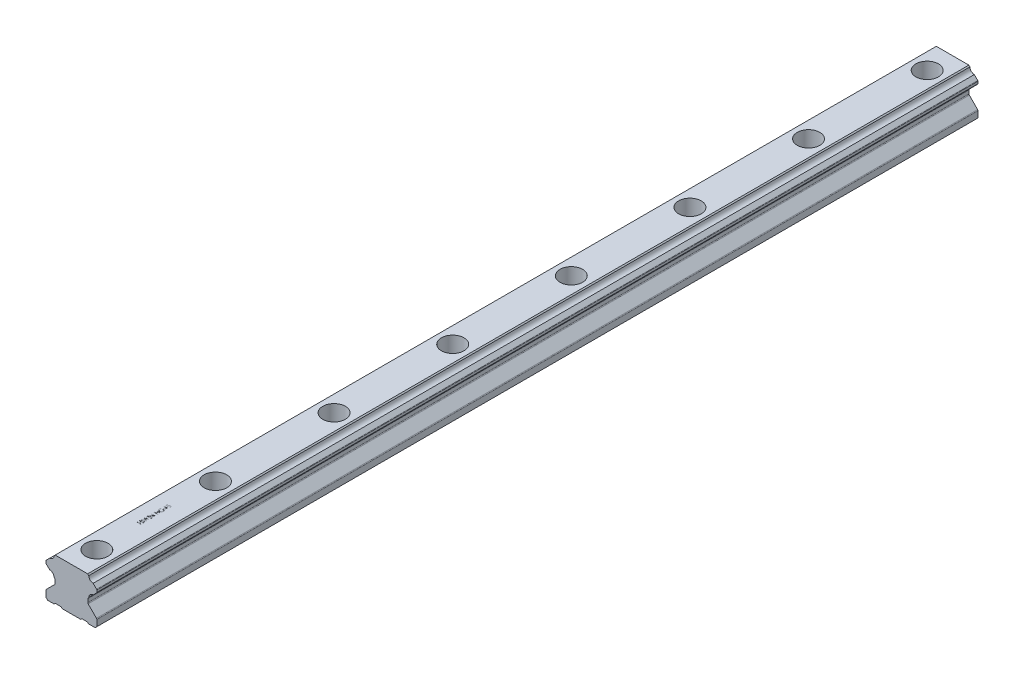
SolidWorks part; units mm, degrees
material "镀铬不锈钢"
ref_plane "前视基准面" through (0, 0, 0) normal (0, 0, 1) x (1, 0, 0)
ref_plane "上视基准面" through (0, 0, 0) normal (0, 1, 0) x (1, 0, 0)
ref_plane "右视基准面" through (0, 0, 0) normal (1, 0, 0) x (0, 0, -1)
sketch "草图1" plane through (0, 0, 0) normal (0, 0, 1) x (1, 0, 0)
  line L28 (-19.2333, 33.1666) -> (-22.2653, 30.1347)
  line L29 (-14.4996, 19.0026) -> (-14.4996, 15.9974)
  line L30 (14.5004, 15.9974) -> (14.5004, 19.0026)
  line L31 (15.3339, 37.0668) -> (14.4007, 38)
  line L32 (-22.2653, 27.2653) -> (-19.2344, 24.2344)
  line L33 (22.5004, 27.831) -> (22.5004, 29.569)
  line L34 (14.8518, 19.8511) -> (15.3339, 20.3331)
  line L35 (22.2661, 30.1347) -> (19.2341, 33.1666)
  line L36 (-22.4996, 29.569) -> (-22.4996, 27.831)
  line L37 (-15.3331, 20.3331) -> (-14.8511, 19.8511)
  line L38 (9.25, 1) -> (14.25, 1)
  line L39 (-14.25, 1) -> (-9.25, 1)
  line L40 (14.25, 1) -> (15.25, 0)
  line L41 (21.0004, 0) -> (22.5004, 1.5)
  line L42 (22.1489, 7.8518) -> (14.8518, 15.1489)
  line L43 (8.25, 0) -> (9.25, 1)
  line L44 (-22.4996, 1.5) -> (-20.9996, 0)
  line L45 (-15.25, 0) -> (-14.25, 1)
  line L46 (-8.25, 0) -> (8.25, 0)
  line L47 (15.25, 0) -> (21.0004, 0)
  line L48 (-14.8511, 15.1489) -> (-22.1482, 7.8518)
  line L49 (-22.4996, 7.0033) -> (-22.4996, 1.5)
  line L50 (-20.9996, 0) -> (-15.25, 0)
  line L51 (-9.25, 1) -> (-8.25, 0)
  line L52 (22.5004, 1.5) -> (22.5004, 7.0033)
  line L53 (14.4007, 38) -> (-14.4, 38)
  line L54 (-14.4, 38) -> (-15.3331, 37.0668)
  line L55 (19.2351, 24.2344) -> (22.2661, 27.2653)
  arc A14 (-19.2333, 33.1666) -> (-15.3331, 37.0668) centre (-19.3319, 37.1654) ccw
  arc A15 (-15.3331, 20.3331) -> (-19.2344, 24.2344) centre (-19.3319, 20.2356) ccw
  arc A16 (14.8518, 19.8511) -> (14.5004, 19.0026) centre (15.7004, 19.0026) ccw
  arc A17 (22.5004, 7.0033) -> (22.1489, 7.8518) centre (21.3004, 7.0033) ccw
  arc A18 (19.2351, 24.2344) -> (15.3339, 20.3331) centre (19.3327, 20.2356) ccw
  arc A19 (22.5004, 29.569) -> (22.2661, 30.1347) centre (21.7004, 29.569) ccw
  arc A20 (-22.4996, 27.831) -> (-22.2653, 27.2653) centre (-21.6996, 27.831) ccw
  arc A21 (-14.8511, 15.1489) -> (-14.4996, 15.9974) centre (-15.6996, 15.9974) ccw
  arc A22 (14.5004, 15.9974) -> (14.8518, 15.1489) centre (15.7004, 15.9974) ccw
  arc A23 (15.3339, 37.0668) -> (19.2341, 33.1666) centre (19.3327, 37.1654) ccw
  arc A24 (-22.2653, 30.1347) -> (-22.4996, 29.569) centre (-21.6996, 29.569) ccw
  arc A25 (-22.1482, 7.8518) -> (-22.4996, 7.0033) centre (-21.2996, 7.0033) ccw
  arc A26 (22.2661, 27.2653) -> (22.5004, 27.831) centre (21.7004, 27.831) ccw
  arc A27 (-14.4996, 19.0026) -> (-14.8511, 19.8511) centre (-15.6996, 19.0026) ccw
extrude "凸台-拉伸1" add sketch "草图1" against normal blind 780
hole_wizard "M12 六角凹头螺钉的柱形沉头孔1" positions "草图3" profile "草图2" counterbore size "M12" standard "ISO" end condition through all
sketch "草图3" plane through (-6.046, 38, -69.0002) normal (0, 1, 0) x (-1, 0, 0)
  point P0 (-6.046, 46.5002)
  dimension "D1" = 22.5
sketch "草图2" plane through (0, 38, -22.5) normal (1, 0, 0) x (0, 0, 1)
  line L0 (0, 0) -> (0, 38)
  line L1 (0, 38) -> (7, 38)
  line L3 (7, 38) -> (7, 17)
  line L4 (7, 17) -> (10, 17)
  line L5 (10, 17) -> (10, 0)
  line L7 (10, 0) -> (0, 0)
  line L11 (0, -6.35) -> (0, 107.95) construction
  dimension "通孔孔直径" = 14
  dimension "通孔孔深度" = 38
  dimension "柱形沉头孔直径" = 20
  dimension "柱形沉头孔深度" = 17
pattern_linear "阵列(线性)1" count 8 spacing 105 along (0, 0, -1) of "M12 六角凹头螺钉的柱形沉头孔1"
sketch "草图6" plane through (0, 38, 0) normal (0, 1, 0) x (1, 0, 0)
  line L0 (0, 22.5) -> (0, 127.5) construction
  text T0 "HIWIN HG45"
extrude "切除-拉伸1" cut sketch "草图6" against normal blind 0.1
equation "\"D1@凸台-拉伸1\" = 2 * \"D1@草图3\" + \"D3@阵列(线性)1\" *  ( \"D1@阵列(线性)1\"  - 1) "
